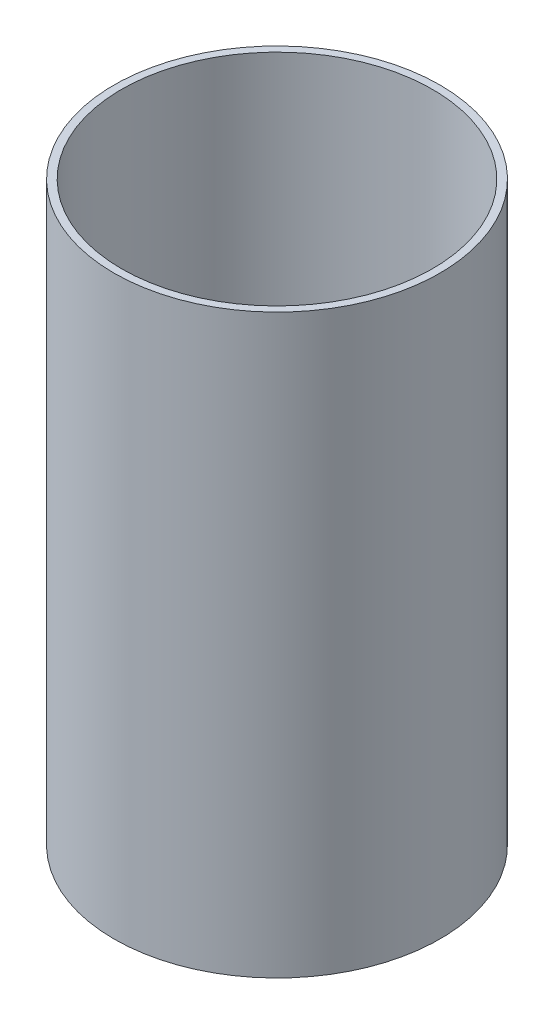
SolidWorks part; units mm, degrees
ref_plane "Front Plane" through (0, 0, 0) normal (0, 0, 1) x (1, 0, 0)
ref_plane "Top Plane" through (0, 0, 0) normal (0, 1, 0) x (1, 0, 0)
ref_plane "Right Plane" through (0, 0, 0) normal (1, 0, 0) x (0, 0, -1)
sketch "Sketch1" plane through (0, 0, 0) normal (0, 1, 0) x (1, 0, 0)
  circle A0 centre (0, 0) radius 32.5
  circle A1 centre (0, 0) radius 31
  dimension "D1" = 65
  dimension "D2" = 62
extrude "Boss-Extrude1" add sketch "Sketch1" along normal blind 115
